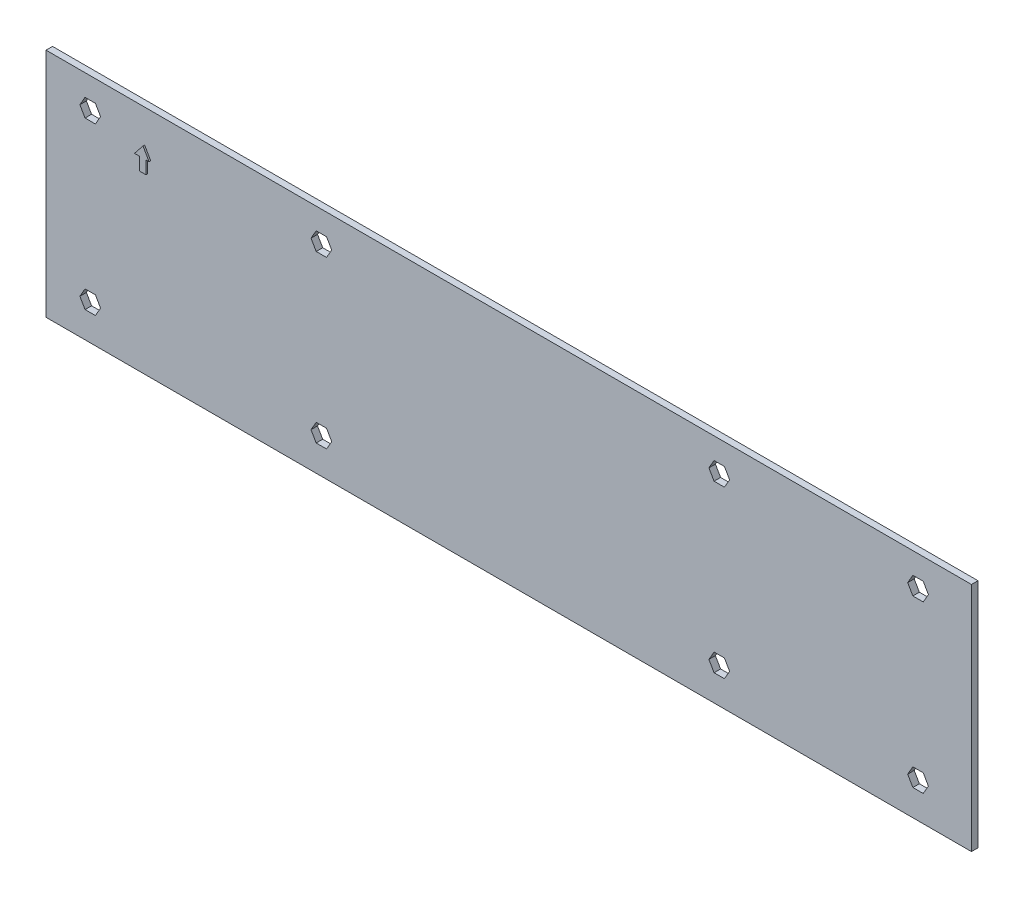
SolidWorks part; units mm, degrees
ref_plane "Front Plane" through (0, 0, 0) normal (0, 0, 1) x (1, 0, 0)
ref_plane "Top Plane" through (0, 0, 0) normal (0, 1, 0) x (1, 0, 0)
ref_plane "Right Plane" through (0, 0, 0) normal (1, 0, 0) x (0, 0, -1)
sketch "Sketch1" plane through (0, 0, 0) normal (0, 0, 1) x (1, 0, 0)
  line L0 (-142.3753, 158.2479) -> (-128.8053, 158.2479) construction
  line L1 (141.6247, 158.2479) -> (125.2247, 158.2479) construction
  line L2 (141.6247, 158.2479) -> (141.6247, 148.9479) construction
  line L3 (141.6247, 148.9479) -> (125.2247, 148.9479) construction
  line L4 (125.2247, 158.2479) -> (125.2247, 148.9479) construction
  line L5 (122.0493, 148.9479) -> (123.637, 146.1979)
  line L6 (123.637, 146.1979) -> (126.8124, 146.1979)
  line L7 (126.8124, 146.1979) -> (128.4001, 148.9479)
  line L8 (128.4001, 148.9479) -> (126.8124, 151.6979)
  line L9 (126.8124, 151.6979) -> (123.637, 151.6979)
  line L10 (123.637, 151.6979) -> (122.0493, 148.9479)
  line L11 (-128.8053, 158.2479) -> (-128.8053, 148.9479) construction
  line L12 (-142.3753, 87.2479) -> (-128.8053, 87.2479) construction
  line L13 (-128.8053, 87.2479) -> (-128.8053, 98.0479) construction
  line L14 (141.6247, 87.2479) -> (125.2247, 87.2479) construction
  line L15 (125.2247, 87.2479) -> (125.2247, 98.0479) construction
  line L16 (-142.3753, 87.2479) -> (-57.8753, 87.2479) construction
  line L17 (122.0493, 98.0479) -> (123.637, 95.2979)
  line L18 (123.637, 95.2979) -> (126.8124, 95.2979)
  line L19 (126.8124, 95.2979) -> (128.4001, 98.0479)
  line L20 (128.4001, 98.0479) -> (126.8124, 100.7979)
  line L21 (126.8124, 100.7979) -> (123.637, 100.7979)
  line L22 (123.637, 100.7979) -> (122.0493, 98.0479)
  line L23 (-131.9807, 98.0479) -> (-130.393, 95.2979)
  line L24 (-130.393, 95.2979) -> (-127.2176, 95.2979)
  line L25 (-127.2176, 95.2979) -> (-125.6299, 98.0479)
  line L26 (-125.6299, 98.0479) -> (-127.2176, 100.7979)
  line L27 (-127.2176, 100.7979) -> (-130.393, 100.7979)
  line L28 (-130.393, 100.7979) -> (-131.9807, 98.0479)
  line L29 (-125.6299, 148.9479) -> (-127.2176, 151.6979)
  line L30 (-127.2176, 151.6979) -> (-130.393, 151.6979)
  line L31 (-130.393, 151.6979) -> (-131.9807, 148.9479)
  line L32 (-131.9807, 148.9479) -> (-130.393, 146.1979)
  line L33 (-130.393, 146.1979) -> (-127.2176, 146.1979)
  line L34 (-127.2176, 146.1979) -> (-125.6299, 148.9479)
  line L35 (-57.8753, 87.2479) -> (-57.8753, 98.0479) construction
  line L36 (141.6247, 87.2479) -> (64.2247, 87.2479) construction
  line L37 (64.2247, 87.2479) -> (64.2247, 98.0479) construction
  line L38 (-142.3753, 158.2479) -> (-57.8753, 158.2479) construction
  line L39 (-61.0507, 98.0479) -> (-59.463, 95.2979)
  line L40 (-59.463, 95.2979) -> (-56.2876, 95.2979)
  line L41 (-56.2876, 95.2979) -> (-54.6999, 98.0479)
  line L42 (-54.6999, 98.0479) -> (-56.2876, 100.7979)
  line L43 (-56.2876, 100.7979) -> (-59.463, 100.7979)
  line L44 (-59.463, 100.7979) -> (-61.0507, 98.0479)
  line L45 (-57.8753, 158.2479) -> (-57.8753, 148.9479) construction
  line L46 (141.6247, 158.2479) -> (64.2247, 158.2479) construction
  line L47 (-61.0507, 148.9479) -> (-59.463, 146.1979)
  line L48 (-59.463, 146.1979) -> (-56.2876, 146.1979)
  line L49 (-56.2876, 146.1979) -> (-54.6999, 148.9479)
  line L50 (-54.6999, 148.9479) -> (-56.2876, 151.6979)
  line L51 (-56.2876, 151.6979) -> (-59.463, 151.6979)
  line L52 (-59.463, 151.6979) -> (-61.0507, 148.9479)
  line L53 (64.2247, 158.2479) -> (64.2247, 148.9479) construction
  line L54 (61.0493, 148.9479) -> (62.637, 146.1979)
  line L55 (62.637, 146.1979) -> (65.8124, 146.1979)
  line L56 (65.8124, 146.1979) -> (67.4001, 148.9479)
  line L57 (67.4001, 148.9479) -> (65.8124, 151.6979)
  line L58 (65.8124, 151.6979) -> (62.637, 151.6979)
  line L59 (62.637, 151.6979) -> (61.0493, 148.9479)
  line L60 (61.0493, 98.0479) -> (62.637, 95.2979)
  line L61 (62.637, 95.2979) -> (65.8124, 95.2979)
  line L62 (65.8124, 95.2979) -> (67.4001, 98.0479)
  line L63 (67.4001, 98.0479) -> (65.8124, 100.7979)
  line L64 (65.8124, 100.7979) -> (62.637, 100.7979)
  line L65 (62.637, 100.7979) -> (61.0493, 98.0479)
  line L66 (-142.3753, 87.2479) -> (-142.3753, 158.2479)
  line L67 (-142.3753, 158.2479) -> (141.6247, 158.2479)
  line L68 (141.6247, 158.2479) -> (141.6247, 87.2479)
  line L69 (141.6247, 87.2479) -> (-142.3753, 87.2479)
  circle A0 centre (125.2247, 148.9479) radius 2.75 construction
  circle A1 centre (125.2247, 98.0479) radius 2.75 construction
  circle A2 centre (-128.8053, 98.0479) radius 2.75 construction
  circle A3 centre (-128.8053, 148.9479) radius 2.75 construction
  circle A4 centre (-57.8753, 98.0479) radius 2.75 construction
  circle A5 centre (-57.8753, 148.9479) radius 2.75 construction
  circle A6 centre (64.2247, 148.9479) radius 2.75 construction
  circle A7 centre (64.2247, 98.0479) radius 2.75 construction
  circle A8 centre (-128.8053, 148.9479) radius 1 construction
  circle A9 centre (-57.8753, 148.9479) radius 1 construction
  circle A10 centre (-128.8053, 98.0479) radius 1 construction
  circle A11 centre (-57.8753, 98.0479) radius 1 construction
  circle A12 centre (64.2247, 98.0479) radius 1 construction
  circle A13 centre (125.2247, 98.0479) radius 1 construction
  circle A14 centre (125.2247, 148.9479) radius 1 construction
  circle A15 centre (64.2247, 148.9479) radius 1 construction
  dimension "D1" = 16.4
  dimension "D2" = 9.3
  dimension "D3" = 10.8
  dimension "D4" = 16.4
  dimension "D5" = 9.3
  dimension "D6" = 13.57
  dimension "D7" = 13.57
  dimension "D8" = 10.8
  dimension "D9" = 10.8
  dimension "D10" = 84.5
  dimension "D11" = 10.8
  dimension "D12" = 77.4
  dimension "D13" = 84.5
  dimension "D14" = 9.3
  dimension "D15" = 77.4
  dimension "D16" = 9.3
extrude "Boss-Extrude1" add sketch "Sketch1" along normal blind 2
sketch "Sketch2" plane through (0, 0, 2) normal (0, 0, 1) x (1, 0, 0)
  line L0 (-113.1484, 140.954) -> (-113.1484, 144.8979)
  line L1 (-113.1484, 144.8979) -> (-114.7111, 144.8979)
  line L2 (-114.7111, 144.8979) -> (-112.1067, 148.172)
  line L3 (-112.1067, 148.172) -> (-110.2463, 144.8979)
  line L4 (-110.2463, 144.8979) -> (-111.1765, 144.8979)
  line L5 (-111.1765, 144.8979) -> (-111.1765, 140.954)
  line L6 (-111.1765, 140.954) -> (-113.1484, 140.954)
extrude "Boss-Extrude2" add sketch "Sketch2" along normal blind 0.5
